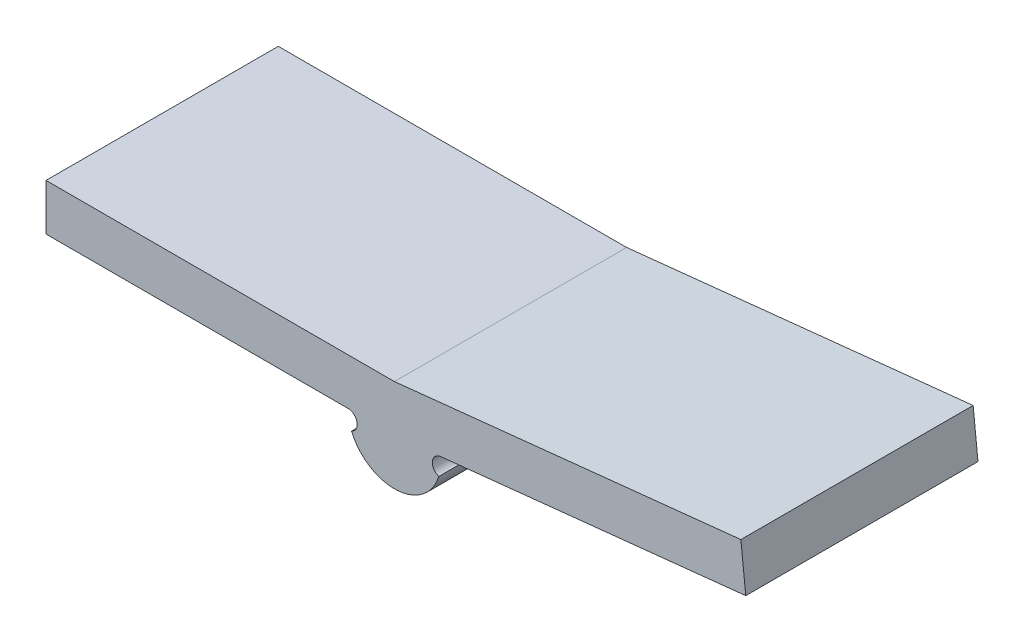
SolidWorks part; units mm, degrees
ref_plane "Front Plane" through (0, 0, 0) normal (0, 0, 1) x (1, 0, 0)
ref_plane "Top Plane" through (0, 0, 0) normal (0, 1, 0) x (1, 0, 0)
ref_plane "Right Plane" through (0, 0, 0) normal (1, 0, 0) x (0, 0, -1)
sketch "Sketch2" plane through (0, 0, 0) normal (0, 0, 1) x (1, 0, 0)
  line L0 (-133.8718, 14.8394) -> (-58.8718, 14.8394)
  line L1 (-58.8718, 14.8394) -> (15.7173, 22.6791)
  line L2 (15.7173, 22.6791) -> (16.7626, 12.7338)
  line L3 (16.7626, 12.7338) -> (-48.921, 5.8302)
  line L5 (-68.8718, 4.8394) -> (-133.8718, 4.8394)
  line L6 (-133.8718, 4.8394) -> (-133.8718, 14.8394)
  arc A0 (-68.8718, 4.8394) -> (-48.921, 5.8302) centre (-58.8718, 4.8394) ccw
  point P6 (-212.8614, 47.4597)
  point P9 (-191.8719, 76.3592)
  dimension "D12" = 10
  dimension "D1" = 75
  dimension "D2" = 75
  dimension "D3" = 90
  dimension "D4" = 90
  dimension "D5" = 90
  dimension "D6" = 90
  dimension "D7" = 10
  dimension "D8" = 10
  dimension "D9" = 10
  dimension "D10" = 174
  dimension "D11" = 75
extrude "Boss-Extrude1" add sketch "Sketch2" along normal blind 50
sketch "Sketch4" plane through (0, 0, 50) normal (0, 0, 1) x (1, 0, 0)
  line L0 (-68.8718, -13.656) -> (-68.8718, 25.1946) construction
  line L1 (-68.8718, 0.8394) -> (-68.8718, 4.8394)
  line L2 (-47.2565, -10.0067) -> (-51.1494, 27.0315) construction
  line L3 (-48.5029, 1.8521) -> (-48.921, 5.8302)
  arc A0 (-68.8718, 0.8394) -> (-68.8718, 4.8394) centre (-68.8718, 2.8394) ccw
  arc A1 (-48.5029, 1.8521) -> (-48.921, 5.8302) centre (-48.712, 3.8412) cw
  dimension "D3" = 2
  dimension "D6" = 2
  dimension "D1" = 0
  dimension "D2" = 0
  dimension "D4" = 6
  dimension "D5" = 0
  dimension "D7" = 0
extrude "Cut-Extrude1" cut sketch "Sketch4" against normal blind 50
